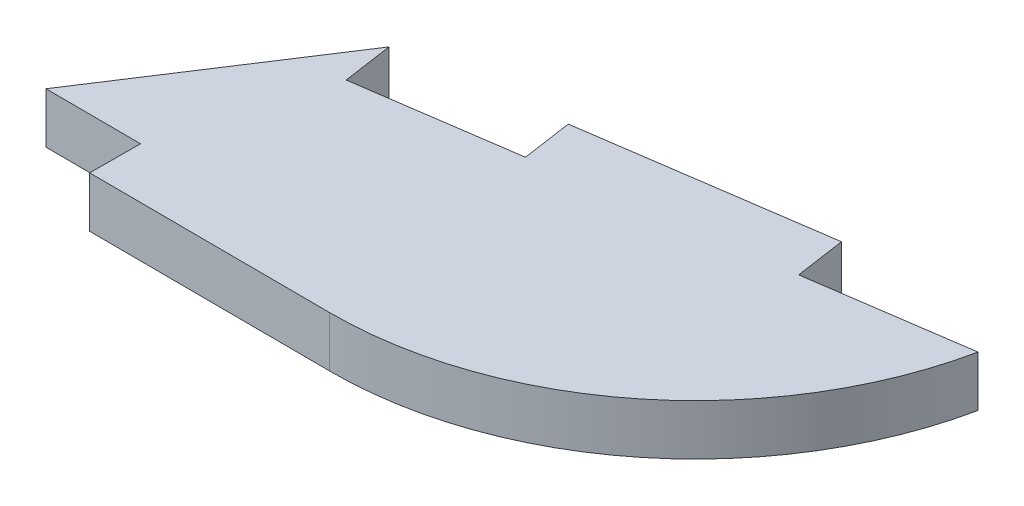
SolidWorks part; units mm, degrees
material "Skleněné vlákno-A"
ref_plane "Přední rovina" through (0, 0, 0) normal (0, 0, 1) x (1, 0, 0)
ref_plane "Horní rovina" through (0, 0, 0) normal (0, 1, 0) x (1, 0, 0)
ref_plane "Pravá rovina" through (0, 0, 0) normal (1, 0, 0) x (0, 0, -1)
sketch "Skica1" plane through (0, 0, 0) normal (0, 1, 0) x (1, 0, 0)
  line L0 (36.7204, 9.7123) -> (25.435, 8.0684) construction
  line L1 (21.591, 1.1146) -> (21.5841, -0.4854)
  line L2 (21.5841, -0.4854) -> (29.204, -0.518)
  line L3 (22.8666, 7.6942) -> (18.591, 1.1275)
  line L4 (18.591, 1.1275) -> (21.591, 1.1146)
  line L5 (23.0972, 6.111) -> (22.8666, 7.6942)
  line L6 (26.2109, 1.0949) -> (17.732, 1.1312) construction
  line L7 (35.5854, 7.9301) -> (35.3548, 9.5133)
  line L8 (35.3548, 9.5133) -> (27.8144, 8.415)
  line L9 (27.8144, 8.415) -> (28.045, 6.8317)
  line L10 (28.045, 6.8317) -> (23.0972, 6.111)
  line L11 (25.6656, 6.4851) -> (36.951, 8.129) construction
  line L12 (36.951, 8.129) -> (111.1678, 18.9398) construction
  line L13 (21.591, 1.1146) -> (21.5841, -0.4854) construction
  line L14 (40.5332, 8.6508) -> (35.5854, 7.9301)
  line L15 (17.732, 1.1312) -> (14.8534, 1.1435) construction
  line L16 (21.591, 1.1146) -> (18.5769, 1.1275) construction
  line L18 (28.045, 6.8317) -> (27.8144, 8.415) construction
  line L19 (35.5854, 7.9301) -> (35.3548, 9.5133) construction
  line L22 (17.7251, -0.4688) -> (26.2041, -0.5051) construction
  arc A0 (29.204, -0.518) -> (40.5332, 8.6508) centre (29.2534, 11.0048) ccw
  dimension "D1" = 3
extrude "Přidat vysunutím1" add sketch "Skica1" along normal mid plane 1.6
sketch "Skica2" plane through (0, 0.8, 0) normal (0, 1, 0) x (1, 0, 0)
  line L0 (18.591, 1.1275) -> (21.591, 1.1146) construction
  line L2 (25.3941, 2.0984) -> (25.3941, 2.141)
  line L3 (27.9341, 2.0875) -> (27.9341, 2.1727)
  line L5 (31.9594, 6.3913) -> (32.0063, 6.069)
  line L7 (28.045, 6.8317) -> (23.0972, 6.111) construction
  line L8 (34.4728, 6.7574) -> (34.5667, 6.1129)
  line L9 (22.8541, 2.1092) -> (29.4459, 6.0252)
  line L10 (25.3941, 2.141) -> (32.0063, 6.069)
  line L11 (27.9341, 2.1727) -> (34.5667, 6.1129)
  line L12 (35.3548, 9.5133) -> (27.8144, 8.415) construction
  line L13 (29.4459, 6.0252) -> (29.0711, 8.598)
  line L14 (31.9594, 6.3913) -> (31.5846, 8.9642)
  line L15 (34.4728, 6.7574) -> (34.0981, 9.3303)
  line L16 (22.8541, 2.1092) -> (22.8541, -0.4908)
  line L17 (21.5841, -0.4854) -> (29.204, -0.518) construction
  line L18 (25.3941, 2.0984) -> (25.3941, -0.5017)
  line L19 (27.9341, 2.0875) -> (27.9341, -0.5125)
  dimension "D2" = 1
  dimension "D4" = 2.54
  dimension "D5" = 1
  dimension "D3" = 2.54
  dimension "D6" = 1
  dimension "D1" = 2.54
  dimension "D7" = 1
  dimension "D8" = 1
  dimension "D9" = 2.54
  dimension "D10" = 1
  dimension "D11" = 1.27
  dimension "D12" = 1.27
